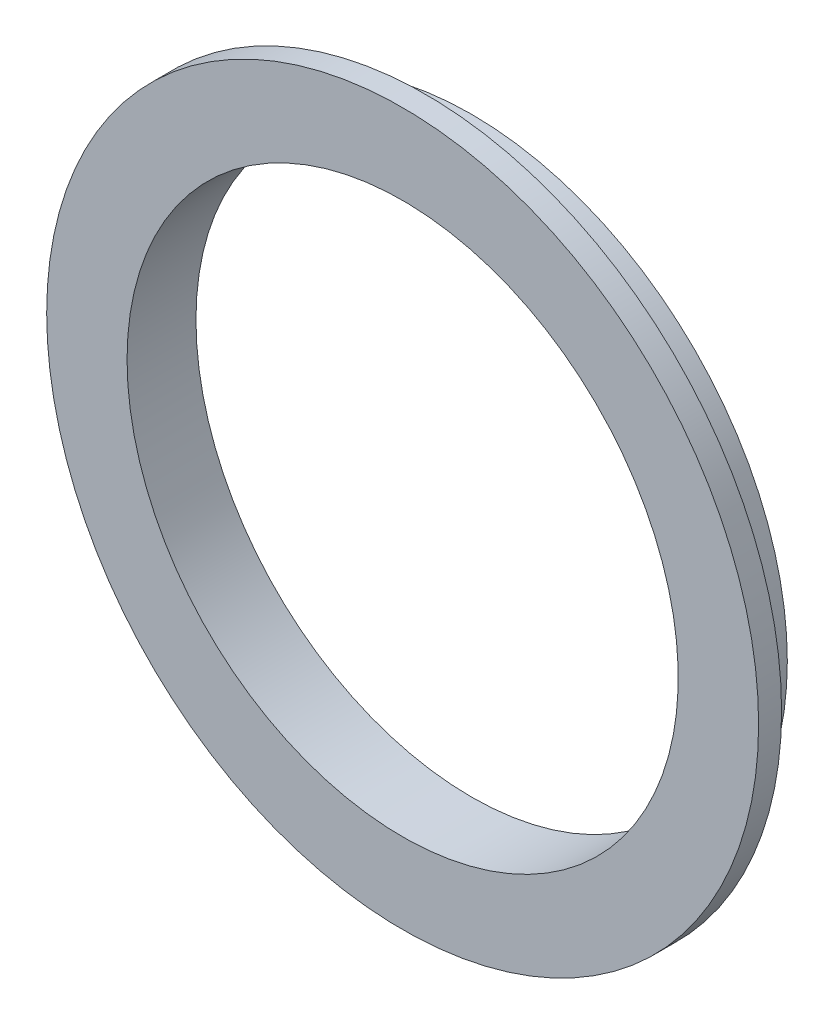
SolidWorks part; units mm, degrees
ref_plane "前视基准面" through (0, 0, 0) normal (0, 0, 1) x (1, 0, 0)
ref_plane "上视基准面" through (0, 0, 0) normal (0, 1, 0) x (1, 0, 0)
ref_plane "右视基准面" through (0, 0, 0) normal (1, 0, 0) x (0, 0, -1)
sketch "草图1" plane through (0, 0, 0) normal (0, 0, 1) x (1, 0, 0)
  circle A0 centre (0, 0) radius 27.5
  circle A1 centre (0, 0) radius 24
  dimension "D1" = 55
  dimension "D2" = 48
extrude "凸台-拉伸1" add sketch "草图1" along normal blind 4
sketch "草图2" plane through (0, 0, 4) normal (0, 0, 1) x (1, 0, 0)
  circle A0 centre (0, 0) radius 31
  dimension "D1" = 62
extrude "凸台-拉伸2" add sketch "草图2" along normal blind 2
sketch "草图3" plane through (0, 0, 4) normal (0, 0, -1) x (-1, 0, 0)
  circle A0 centre (0, 0) radius 24
extrude "切除-拉伸1" cut sketch "草图3" against normal blind 2
